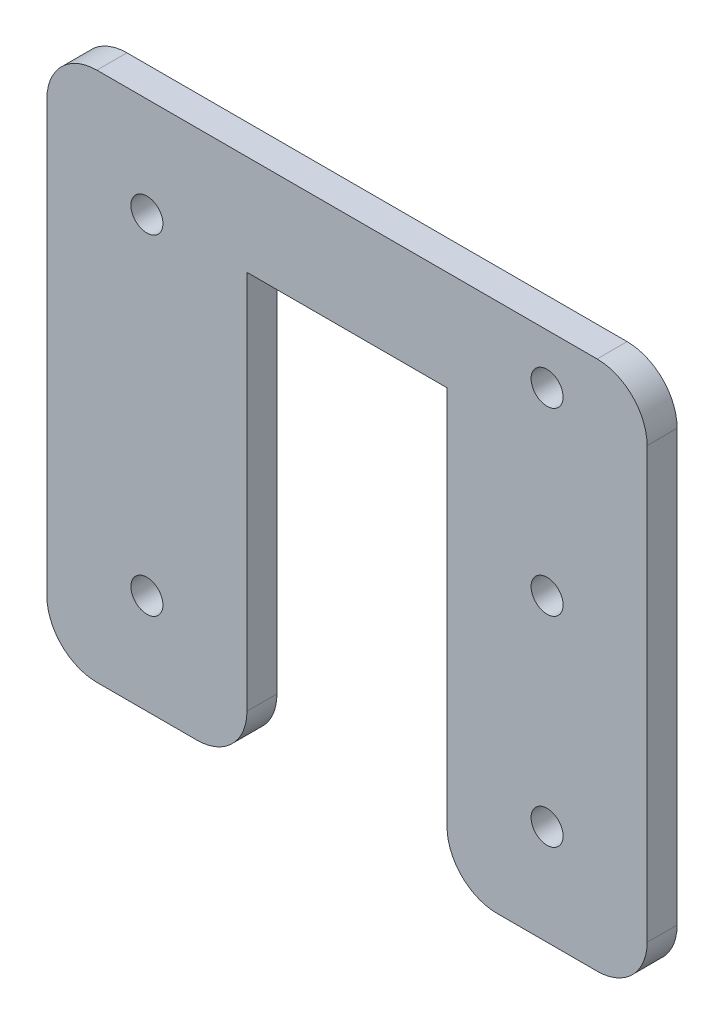
SolidWorks part; units mm, degrees
material "Thornel Mat VMA"
ref_plane "前视基准面" through (0, 0, 0) normal (0, 0, 1) x (1, 0, 0)
ref_plane "上视基准面" through (0, 0, 0) normal (0, 1, 0) x (1, 0, 0)
ref_plane "右视基准面" through (0, 0, 0) normal (1, 0, 0) x (0, 0, -1)
other "Configuration Table"
sketch "草图1" plane through (0, 0, 0) normal (0, 0, 1) x (1, 0, 0)
  line L1 (0, 0) -> (60, 0)
  line L2 (0, 0) -> (0, 53)
  line L3 (0, 53) -> (60, 53)
  line L4 (60, 0) -> (60, 53)
  dimension "D1" = 60
  dimension "D2" = 53
extrude "凸台-拉伸1" add sketch "草图1" along normal blind 3
sketch "草图2" plane through (0, 0, 3) normal (0, 0, 1) x (1, 0, 0)
  line L0 (0, 0) -> (60, 0) construction
  line L1 (20, 0) -> (40, 0)
  line L2 (20, 0) -> (20, 43)
  line L3 (20, 43) -> (40, 43)
  line L4 (40, 0) -> (40, 43)
  line L5 (60, 0) -> (60, 53) construction
  dimension "D1" = 20
  dimension "D2" = 43
  dimension "D3" = 20
extrude "切除-拉伸1" cut sketch "草图2" against normal through all
sketch "草图3" plane through (0, 0, 3) normal (0, 0, 1) x (1, 0, 0)
  line L0 (50, 0) -> (50, 53) construction
  line L1 (40, 0) -> (60, 0) construction
  line L2 (60, 53) -> (0, 53) construction
  circle A0 centre (50, 10) radius 1.6
  circle A1 centre (50, 30) radius 1.6
  circle A2 centre (50, 48) radius 1.6
  dimension "D1" = 3.2
  dimension "D2" = 10
  dimension "D3" = 30
  dimension "D4" = 18
extrude "切除-拉伸2" cut sketch "草图3" against normal through all
sketch "草图4" plane through (0, 0, 3) normal (0, 0, 1) x (1, 0, 0)
  line L0 (10, 0) -> (10, 10) construction
  line L1 (0, 0) -> (20, 0) construction
  circle A0 centre (10, 10) radius 1.6
  dimension "D1" = 3.2
  dimension "D2" = 10
extrude "切除-拉伸3" cut sketch "草图4" against normal through all
fillet "圆角1" radius 5 6 edges at (0, 0, 1.5) (60, 53, 1.5) (60, 0, 1.5) (40, 0, 1.5) (20, 0, 1.5) (0, 53, 1.5)
sketch "草图5" plane through (0, 0, 3) normal (0, 0, 1) x (1, 0, 0)
  line L0 (10, 0) -> (10, 53) construction
  line L1 (5, 0) -> (15, 0) construction
  line L2 (55, 53) -> (5, 53) construction
  circle A0 centre (10, 43) radius 1.6
  dimension "D1" = 3.2
  dimension "D2" = 10
extrude "切除-拉伸4" cut sketch "草图5" against normal through all
